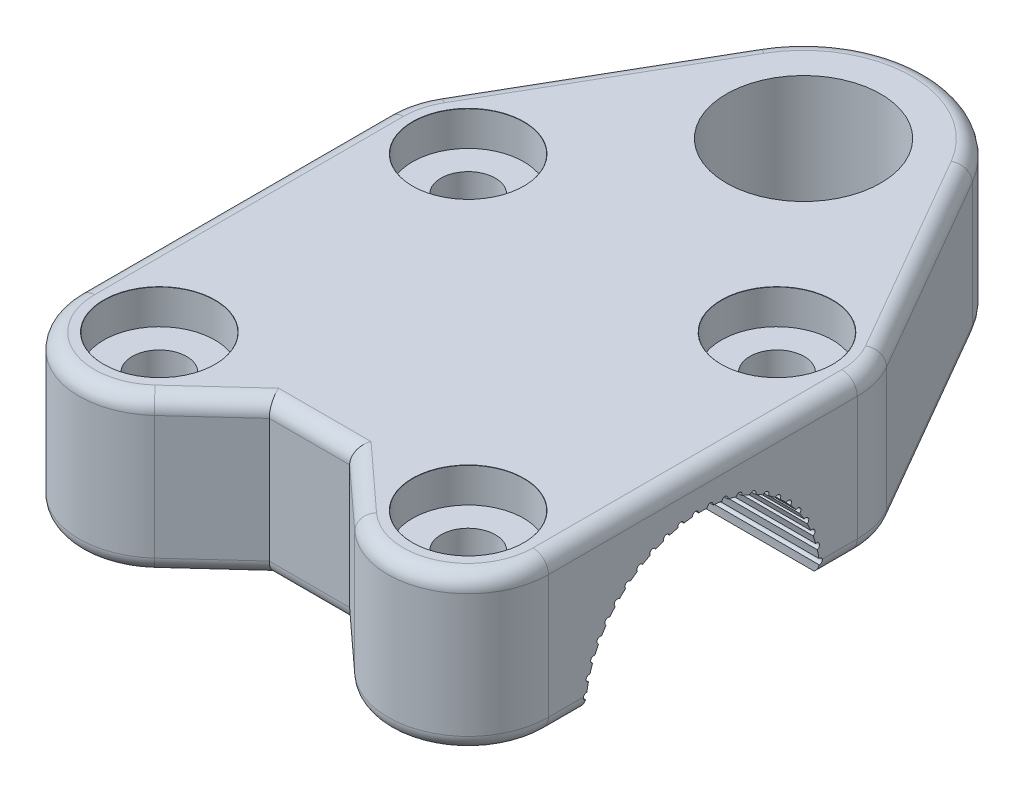
SolidWorks part; units mm, degrees
ref_plane "Front Plane" through (0, 0, 0) normal (0, 0, 1) x (1, 0, 0)
ref_plane "Top Plane" through (0, 0, 0) normal (0, 1, 0) x (1, 0, 0)
ref_plane "Right Plane" through (0, 0, 0) normal (1, 0, 0) x (0, 0, -1)
sketch "Sketch1" plane through (0, 0, 0) normal (0, 1, 0) x (1, 0, 0)
  line L0 (0, 0) -> (0, 40.8319) construction
  line L1 (6.5, 0) -> (-6.5, 0)
  line L2 (-6.5, 0) -> (-16.2272, -8.8949)
  line L3 (-38, 0.6987) -> (-38, 50.6987)
  line L4 (-36.2583, 57.1987) -> (-17.3205, 90)
  line L5 (-38, 50.6987) -> (-38, 98.5935) construction
  line L6 (6.5, 0) -> (16.2272, -8.8949)
  line L7 (38, 0.6987) -> (38, 50.6987)
  line L8 (36.2583, 57.1987) -> (17.3205, 90)
  arc A0 (-16.2272, -8.8949) -> (-38, 0.6987) centre (-25, 0.6987) cw
  arc A1 (-38, 50.6987) -> (-36.2583, 57.1987) centre (-25, 50.6987) cw
  arc A2 (-17.3205, 90) -> (17.3205, 90) centre (0, 80) cw
  arc A3 (16.2272, -8.8949) -> (38, 0.6987) centre (25, 0.6987) ccw
  arc A4 (38, 50.6987) -> (36.2583, 57.1987) centre (25, 50.6987) ccw
  dimension "D3" = 13
  dimension "D5" = 13
  dimension "D6" = 20
  dimension "D1" = 13
  dimension "D2" = 50
  dimension "D4" = 50
  dimension "D7" = 30
  dimension "D8" = 80
extrude "Boss-Extrude1" add sketch "Sketch1" along normal blind 25
hole_wizard "CBORE for M8 Hex Head Bolt1" positions "3DSketch1" profile "Sketch2" counterbore size "M8" standard "ANSI Metric" end condition through all
sketch3d "3DSketch1"
  arc A0 (-38, 25, -0.6987) -> (-16.2272, 25, 8.8949) centre (-25, 25, -0.6987) ccw construction
  point P0 (-25, 25, -0.6987)
  point P6 (-25, 38, -0.6987)
sketch "Sketch2" plane through (-25, 25, -0.6987) normal (1, 0, 0) x (0, 0, 1)
  line L0 (0, 0) -> (0, 25)
  line L1 (0, 25) -> (4.4, 25)
  line L3 (4.4, 25) -> (4.4, 5.6)
  line L4 (9, 5.6) -> (4.4, 5.6)
  line L5 (9, 5.6) -> (9, 0.03)
  line L6 (9, 0.03) -> (9.03, 0)
  line L7 (9.03, 0) -> (0, 0)
  line L8 (-9, 0.03) -> (-9.03, 0) construction
  line L11 (0, -6.35) -> (0, 107.95) construction
  dimension "Thru Hole Dia." = 8.8
  dimension "Thru Hole Depth" = 25
  dimension "C'Bore Dia." = 18
  dimension "C'Bore Depth" = 5.6
  dimension "Near C'Sink Dia." = 18.06
  dimension "Near C'Sink Angle" = 90
pattern_linear "LPattern1" count 2 spacing 50 along (1, 0, 0) count 2 spacing 50 along (0, 0, -1) of "CBORE for M8 Hex Head Bolt1"
sketch "Sketch3" plane through (0, 25, 0) normal (0, 1, 0) x (1, 0, 0)
  circle A0 centre (0, 80) radius 12.5
  dimension "D1" = 25
extrude "Cut-Extrude1" cut sketch "Sketch3" against normal through all
sketch "Sketch4" plane through (38, 0, 0) normal (1, 0, 0) x (0, 0, -1)
  line L0 (0.6987, 0) -> (50.6987, 0) construction
  line L1 (6.6987, 0) -> (44.6987, 0) construction
  arc A0 (44.6987, 0) -> (6.6987, 0) centre (25.6987, 0) ccw
  dimension "D2" = 19
  dimension "D1" = 38
extrude "Cut-Extrude2" cut sketch "Sketch4" against normal through all and the other way through all
sketch "Sketch5" plane through (38, 0, 0) normal (1, 0, 0) x (0, 0, -1)
  circle A0 centre (6.6987, 0) radius 0.5
  dimension "D1" = 1
extrude "Cut-Extrude3" cut sketch "Sketch5" against normal through all
pattern_circular "CirPattern1" count 26 over 180 about axis through (0, 0, -25.6987) along (1, 0, 0) of "Cut-Extrude3"
fillet "Fillet4" radius 2.5 12 edges at (11.3636, 25, 4.4475) (38, 25, -25.6987) (26.7894, 25, -73.5994) (-26.7894, 25, -73.5994) (-11.3636, 25, 4.4475) (0, 25, 0) (-38, 25, -25.6987) (30.2418, 25, 11.1976) (37.557, 25, -54.0634) (0, 25, -100) (-37.557, 25, -54.0634) (-30.2418, 25, 11.1976)
fillet "Fillet5" radius 2.5 14 edges at (38, 0, -47.9487) (37.557, 0, -54.0634) (-38, 0, -47.9487) (-37.557, 0, -54.0634) (-26.7894, 0, -73.5994) (0, 0, -100) (-38, 0, -3.4487) (-30.2418, 0, 11.1976) (38, 0, -3.4487) (30.2418, 0, 11.1976) (26.7894, 0, -73.5994) (-11.3636, 0, 4.4475) (11.3636, 0, 4.4475) (0, 0, 0)
